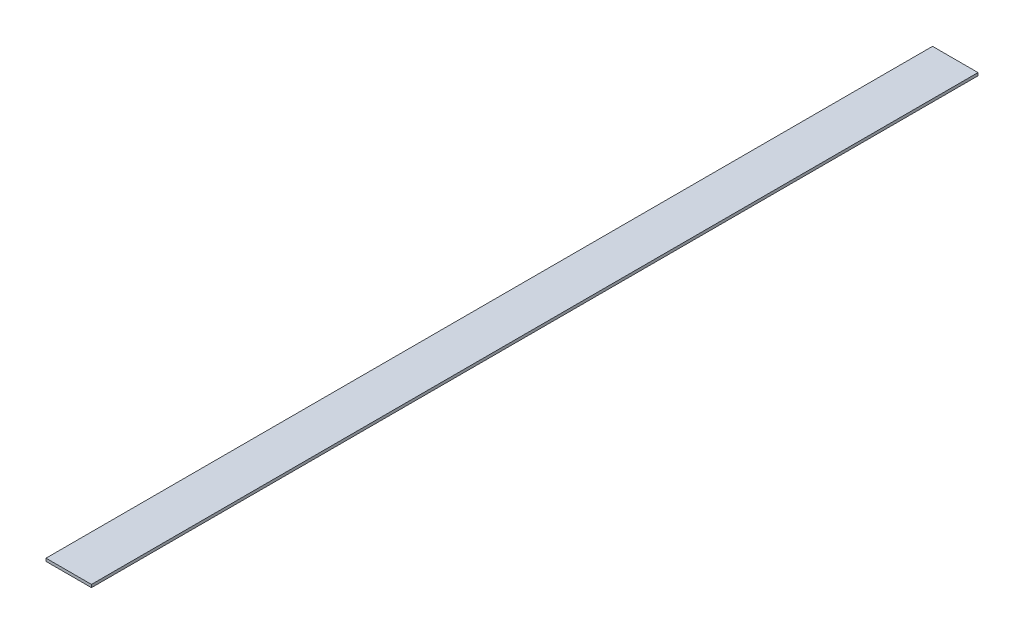
SolidWorks part; units mm, degrees
ref_plane "Front Plane" through (0, 0, 0) normal (0, 0, 1) x (1, 0, 0)
ref_plane "Top Plane" through (0, 0, 0) normal (0, 1, 0) x (1, 0, 0)
ref_plane "Right Plane" through (0, 0, 0) normal (1, 0, 0) x (0, 0, -1)
sketch "Sketch1" plane through (0, 0, 0) normal (0, 1, 0) x (1, 0, 0)
  line L1 (-25.4, -495.3) -> (25.4, -495.3)
  line L2 (-25.4, -495.3) -> (-25.4, 495.3)
  line L3 (-25.4, 495.3) -> (25.4, 495.3)
  line L4 (25.4, -495.3) -> (25.4, 495.3)
  line L5 (-25.4, -495.3) -> (25.4, 495.3) construction
  line L6 (-25.4, 495.3) -> (25.4, -495.3) construction
  point P0 (0, 0)
  dimension "D1" = 50.8
  dimension "D2" = 990.6
extrude "Boss-Extrude1" add sketch "Sketch1" along normal blind 3.175
